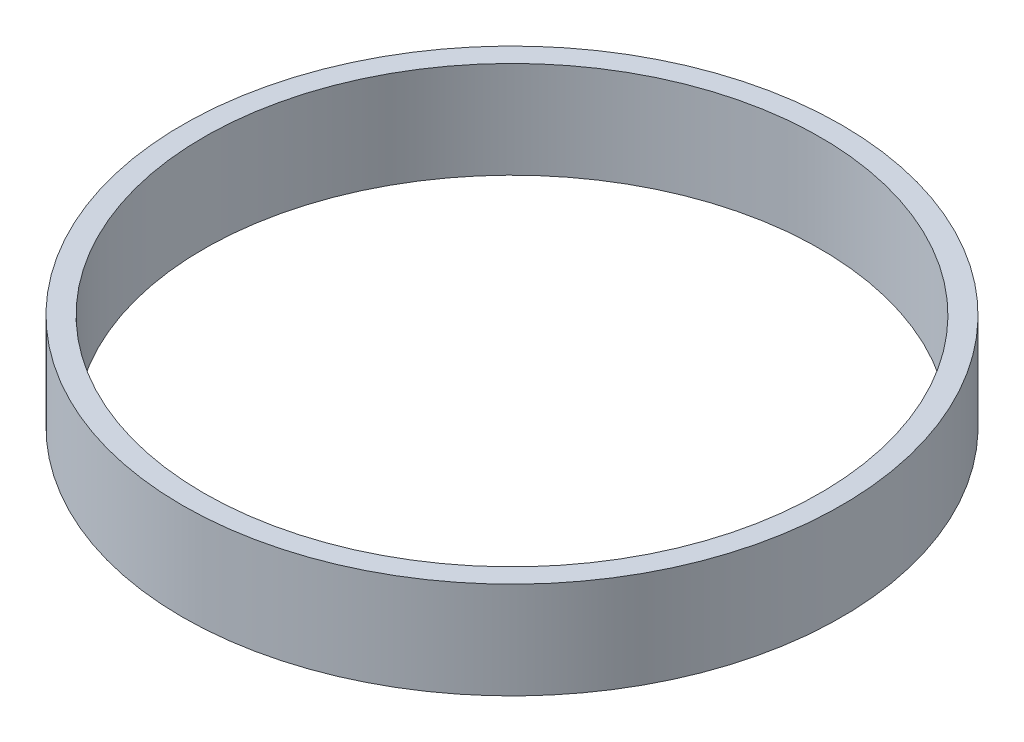
SolidWorks part; units mm, degrees
ref_plane "Front Plane" through (0, 0, 0) normal (0, 0, 1) x (1, 0, 0)
ref_plane "Top Plane" through (0, 0, 0) normal (0, 1, 0) x (1, 0, 0)
ref_plane "Right Plane" through (0, 0, 0) normal (1, 0, 0) x (0, 0, -1)
sketch "Sketch1" plane through (0, 0, 0) normal (0, 1, 0) x (1, 0, 0)
  circle A0 centre (0, 0) radius 31.85
  circle A1 centre (0, 0) radius 34.05
  dimension "D1" = 63.7
  dimension "D2" = 68.1
extrude "Boss-Extrude1" add sketch "Sketch1" along normal blind 10
